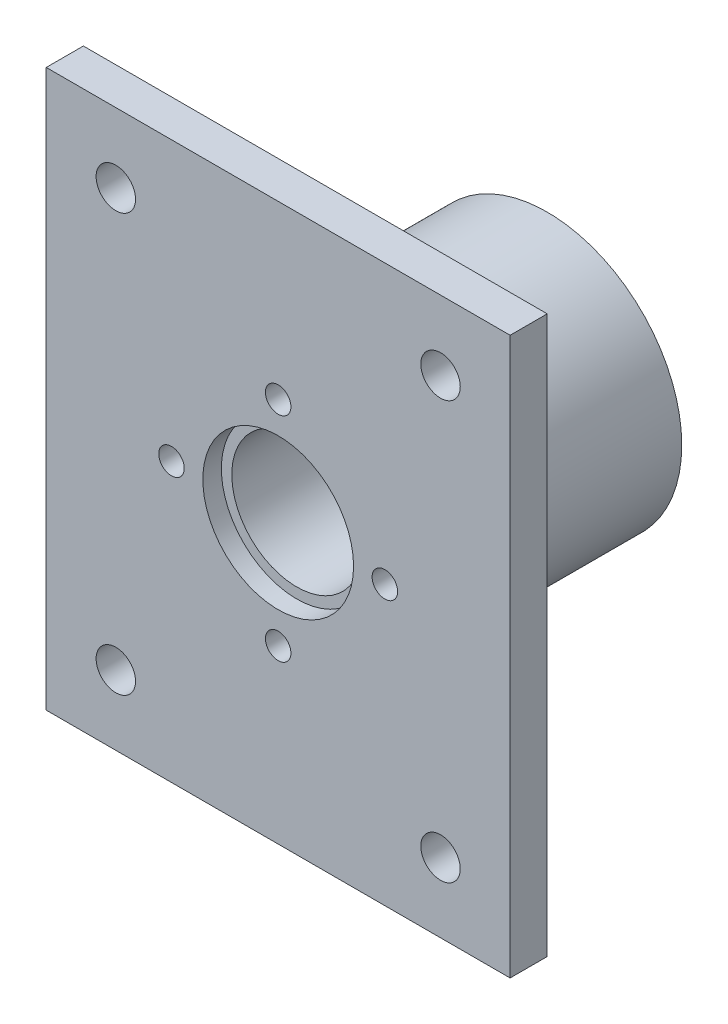
SolidWorks part; units mm, degrees
ref_plane "Front Plane" through (0, 0, 0) normal (0, 0, 1) x (1, 0, 0)
ref_plane "Top Plane" through (0, 0, 0) normal (0, 1, 0) x (1, 0, 0)
ref_plane "Right Plane" through (0, 0, 0) normal (1, 0, 0) x (0, 0, -1)
sketch "Sketch1" plane through (0, 0, 0) normal (0, 0, 1) x (1, 0, 0)
  line L1 (50, -60) -> (-50, -60)
  line L2 (50, -60) -> (50, 60)
  line L3 (50, 60) -> (-50, 60)
  line L4 (-50, -60) -> (-50, 60)
  line L5 (50, -60) -> (-50, 60) construction
  line L6 (50, 60) -> (-50, -60) construction
  point P0 (0, 0)
  dimension "D1" = 100
  dimension "D2" = 120
extrude "Boss-Extrude1" add sketch "Sketch1" along normal blind 8
sketch "Sketch2" plane through (0, 0, 8) normal (0, 0, 1) x (1, 0, 0)
  line L0 (50, -60) -> (50, 60) construction
  line L1 (50, 60) -> (-50, 60) construction
  circle A0 centre (35, 45) radius 4.25
  dimension "D1" = 8.5
  dimension "D2" = 15
  dimension "D3" = 15
extrude "Cut-Extrude1" cut sketch "Sketch2" against normal blind 8
mirror "Mirror1" about plane through (0, 0, 0) normal (1, 0, 0) of "Cut-Extrude1"
mirror "Mirror2" about plane through (0, 0, 0) normal (0, 1, 0) of "Cut-Extrude1", "Mirror1"
sketch "Sketch3" plane through (0, 0, 8) normal (0, 0, 1) x (1, 0, 0)
  circle A0 centre (0, 0) radius 16.25
  dimension "D1" = 32.5
extrude "Cut-Extrude2" cut sketch "Sketch3" against normal blind 4
sketch "Sketch4" plane through (0, 0, 0) normal (0, 0, -1) x (-1, 0, 0)
  circle A0 centre (0, 0) radius 29
  dimension "D1" = 58
extrude "Boss-Extrude2" add sketch "Sketch4" along normal blind 50
sketch "Sketch5" plane through (0, 0, 8) normal (0, 0, 1) x (1, 0, 0)
  circle A1 centre (0, 0) radius 23 construction
  circle A2 centre (0, 23) radius 2.75
  circle A3 centre (23, 0) radius 2.75
  circle A4 centre (0, -23) radius 2.75
  circle A5 centre (-23, 0) radius 2.75
  dimension "D1" = 46
  dimension "D2" = 5.5
  dimension "D3" = 5.5
  dimension "D4" = 5.5
  dimension "D5" = 5.5
extrude "Cut-Extrude3" cut sketch "Sketch5" against normal blind 70
sketch "Sketch6" plane through (0, 0, 4) normal (0, 0, 1) x (1, 0, 0)
  circle A0 centre (0, 0) radius 14
  dimension "D1" = 28
extrude "Cut-Extrude4" cut sketch "Sketch6" against normal blind 31
sketch "Sketch7" plane through (0, 0, -27) normal (0, 0, 1) x (1, 0, 0)
  circle A0 centre (0, 0) radius 12.5
  dimension "D1" = 25
extrude "Cut-Extrude5" cut sketch "Sketch7" against normal blind 61
sketch "Sketch8" plane through (0, 0, -50) normal (0, 0, -1) x (-1, 0, 0)
  circle A0 centre (0, 23) radius 4.15
  circle A1 centre (23, 0) radius 4.15
  circle A2 centre (0, -23) radius 4.15
  circle A3 centre (-23, 0) radius 4.15
  dimension "D1" = 8.3
  dimension "D2" = 8.3
  dimension "D3" = 8.3
  dimension "D4" = 8.3
extrude "Cut-Extrude6" cut sketch "Sketch8" against normal blind 6
sketch "Sketch9" plane through (0, 0, -50) normal (0, 0, -1) x (-1, 0, 0)
  circle A0 centre (0, 0) radius 14
  dimension "D1" = 28
extrude "Cut-Extrude7" cut sketch "Sketch9" against normal blind 8.5
